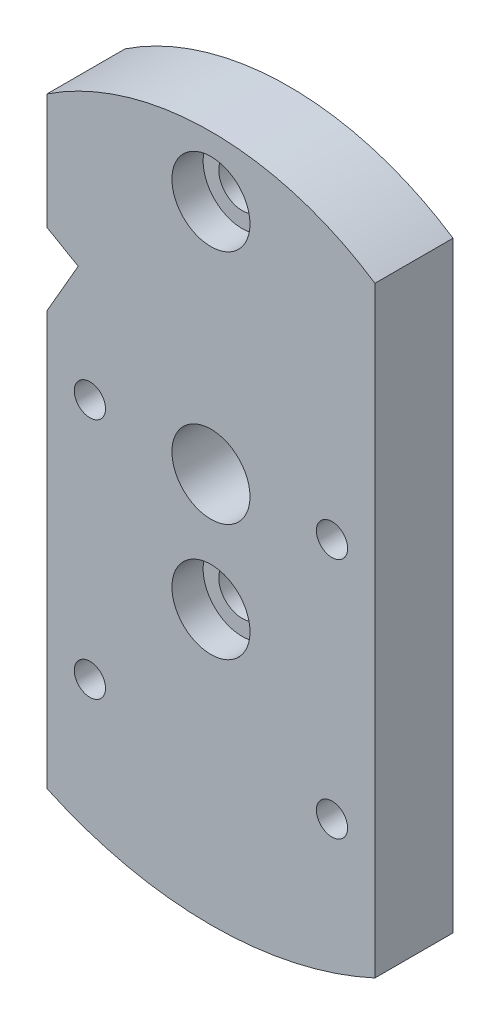
SolidWorks part; units mm, degrees
material "3.3547 (EN-AW 5083)"
ref_plane "Ebene vorne" through (0, 0, 0) normal (0, 0, 1) x (1, 0, 0)
ref_plane "Ebene oben" through (0, 0, 0) normal (0, 1, 0) x (1, 0, 0)
ref_plane "Ebene rechts" through (0, 0, 0) normal (1, 0, 0) x (0, 0, -1)
sketch "Skizze1" plane through (0, 0, 0) normal (0, 0, 1) x (1, 0, 0)
  line L0 (-28.1738, -45.853) -> (-28.1738, -55.2292)
  line L2 (-28.1738, 21.8172) -> (-28.1738, -45.853)
  line L4 (13.8262, 21.8172) -> (13.8262, -45.853)
  line L9 (-22.6738, -40.353) -> (8.3262, -40.353) construction
  line L10 (-22.6738, -40.353) -> (-22.6738, -9.353) construction
  line L11 (-22.6738, -9.353) -> (8.3262, -9.353) construction
  line L12 (8.3262, -40.353) -> (8.3262, -9.353) construction
  line L13 (-7.1738, -9.353) -> (-7.1738, -40.353) construction
  line L14 (-22.6738, -24.853) -> (8.3262, -24.853) construction
  line L15 (13.8262, -45.853) -> (13.8262, -55.2292)
  circle A0 centre (-7.1738, -24.853) radius 3
  circle A1 centre (-7.1738, -9.853) radius 5
  circle A2 centre (-22.6738, -9.353) radius 2
  circle A3 centre (-22.6738, -40.353) radius 2
  circle A4 centre (8.3262, -40.353) radius 2
  circle A5 centre (8.3262, -9.353) radius 2
  arc A6 (-28.1738, -55.2292) -> (13.8262, -55.2292) centre (-7.1738, -9.853) ccw
  circle A7 centre (-7.1738, 20.377) radius 3
  arc A9 (13.8262, 21.8172) -> (-28.1738, 21.8172) centre (-7.1738, -9.853) ccw
  dimension "D2" = 31
  dimension "D6" = 15
  dimension "D8" = 30.23
  dimension "D5" = 50
  dimension "D7" = 38
  dimension "D1" = 42
  dimension "D3" = 31
  dimension "D4" = 21
extrude "Aufsatz-Linear austragen1" add sketch "Skizze1" along normal blind 10
sketch "Skizze2" plane through (0, 0, 10) normal (0, 0, 1) x (1, 0, 0)
  circle A0 centre (-7.1738, -24.853) radius 5
  circle A1 centre (-7.1738, 20.377) radius 5
extrude "Schnitt-Linear austragen1" cut sketch "Skizze2" against normal blind 4
sketch "Skizze3" plane through (0, 0, 0) normal (0, 0, -1) x (-1, 0, 0)
  circle A0 centre (22.6948, -40.332) radius 3
  circle A1 centre (-8.3262, -40.353) radius 3
  circle A2 centre (22.6738, -9.353) radius 3
  circle A3 centre (-8.3472, -9.3741) radius 3
extrude "Schnitt-Linear austragen2" cut sketch "Skizze3" against normal blind 5
sketch "Skizze4" plane through (0, 0, 10) normal (0, 0, 1) x (1, 0, 0)
  line L0 (-7.1738, 20.377) -> (-7.1738, 12.4573) construction
  line L1 (-7.1738, 20.377) -> (-14.2748, 20.377) construction
sketch "Skizze5" plane through (0, 0, 10) normal (0, 0, 1) x (1, 0, 0)
  line L0 (-7.1738, -9.853) -> (-36.6038, 7.1384) construction
  line L2 (-7.1738, -9.853) -> (-40.7949, -9.853) construction
  line L3 (-28.1738, -2.2261) -> (-24.1738, 4.7021)
  line L4 (-28.1738, 21.8172) -> (-28.1738, -55.2292) construction
  line L5 (-24.1738, 4.7021) -> (-28.1738, 7.0115)
  line L6 (-28.1738, 7.0115) -> (-28.1738, -2.2261)
  circle A0 centre (-7.1738, -9.853) radius 5 construction
  dimension "D2" = 22
  dimension "D1" = 30
  dimension "D3" = 8
extrude "Schnitt-Linear austragen3" cut sketch "Skizze5" against normal blind 10
sketch "Skizze6" plane through (-20.1664, 11.6431, 0) normal (-0.866, 0.5, 0) x (0, 0, 1)
  circle A0 centre (5, -12.0147) radius 1.5
extrude "Schnitt-Linear austragen4" cut sketch "Skizze6" against normal blind 20
hole_wizard "M4 Gewindebohrung3" positions "3D-Skizze1" profile "Skizze8" tap size "M4" standard "DIN"
sketch3d "3D-Skizze1"
  line L0 (-11.2221, -7.3943, 5) -> (-26.1738, 1.238, 5) construction
  point P0 (-26.1738, 1.238, 5)
sketch "Skizze8" plane through (-26.1738, 1.238, 5) normal (0, 0, 1) x (-0.5, -0.866, 0)
  line L0 (0, 0) -> (0, 20.9914)
  line L1 (0, 20.9914) -> (1.65, 20)
  line L2 (1.65, 20) -> (1.65, 0.375)
  line L3 (1.65, 0.375) -> (2.025, 0)
  line L5 (2.025, 0) -> (0, 0)
  line L6 (-1.65, 0.375) -> (-2.025, 0) construction
  line L10 (0, 20.9914) -> (-1.65, 20) construction
  line L11 (0, -6.35) -> (0, 107.95) construction
  dimension "Bohrerdurchmesser" = 3.3
  dimension "Bohrungstiefe" = 20
  dimension "Senkdurchmesser (Oben)" = 4.05
  dimension "Senkwinkel (Oben)" = 90
  dimension "Spitzenwinkel" = 118
cosmetic thread "Bohrungsgewinde1" parameters "D1"=17.3182, "D2"=4
